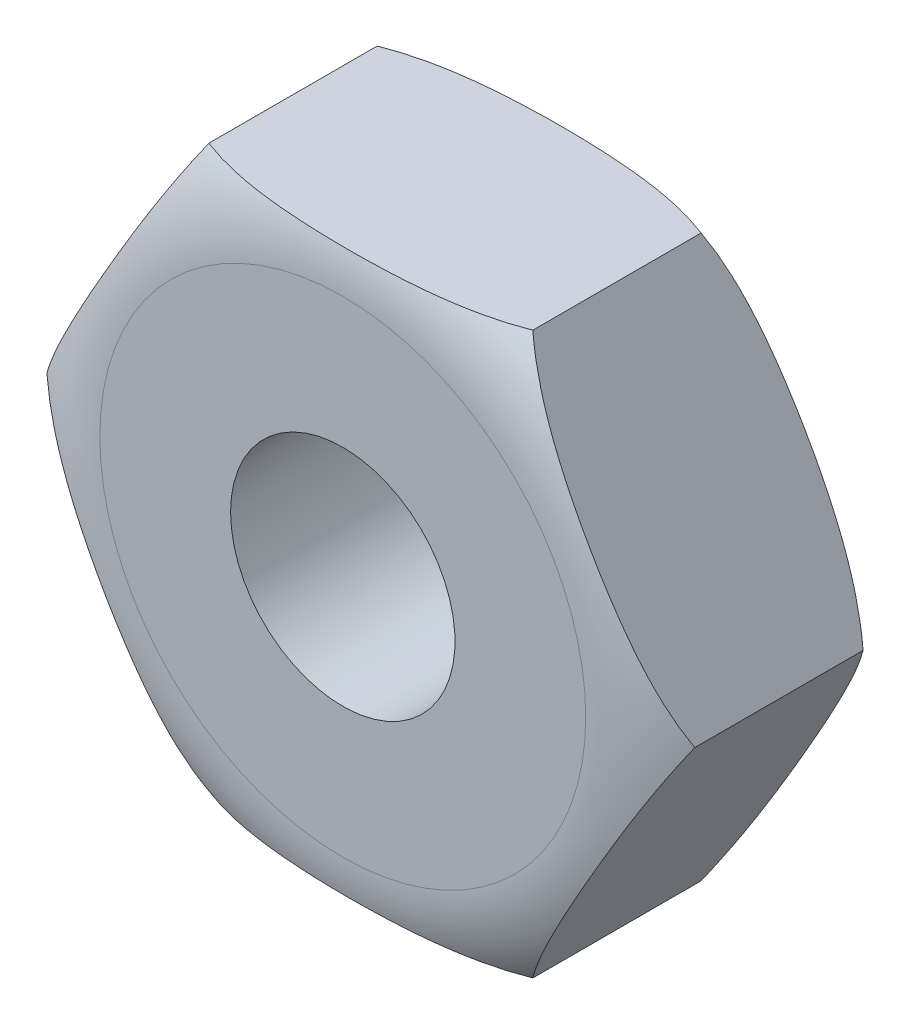
SolidWorks part; units mm, degrees
material "AISI 304"
ref_plane "前视基准面" through (0, 0, 0) normal (0, 0, 1) x (1, 0, 0)
ref_plane "上视基准面" through (0, 0, 0) normal (0, 1, 0) x (1, 0, 0)
ref_plane "右视基准面" through (0, 0, 0) normal (1, 0, 0) x (0, 0, -1)
sketch "草图1" plane through (0, 0, 0) normal (0, 0, 1) x (1, 0, 0)
  line L1 (1.1547, 2) -> (-1.1547, 2)
  line L2 (-1.1547, 2) -> (-2.3094, 0)
  line L3 (-2.3094, 0) -> (-1.1547, -2)
  line L4 (-1.1547, -2) -> (1.1547, -2)
  line L5 (1.1547, -2) -> (2.3094, 0)
  line L6 (2.3094, 0) -> (1.1547, 2)
  circle A0 centre (0, 0) radius 2 construction
  dimension "六角对边" = 4
extrude "螺母的厚度" add sketch "草图1" along normal mid plane 1.6
sketch "草图2" plane through (0, 0, 0) normal (0, 1, 0) x (1, 0, 0)
  line L0 (2.3094, -0.8) -> (2.3094, 0.8) construction
  line L2 (1.7321, 0.8) -> (2.3094, 0.8)
  line L3 (2.3094, 0.8) -> (2.3094, 0.6)
  line L4 (0, 0) -> (0, 0.9918) construction
  line L5 (0, 0) -> (1.8404, 0) construction
  line L6 (2.3094, -0.8) -> (2.3094, -0.6)
  line L7 (1.7321, -0.8) -> (2.3094, -0.8)
  line L8 (2.3094, -0.8) -> (1.1547, -0.8) construction
  arc A0 (2.3094, 0.6) -> (1.7321, 0.8) centre (1.7321, -0.1333) ccw
  arc A1 (2.3094, -0.6) -> (1.7321, -0.8) centre (1.7321, 0.1333) cw
  dimension "D2" = 0.2
revolve "切除-旋转1" cut sketch "草图2" angle 360 about L4
hole_wizard " 螺纹孔1" positions "草图3" profile "草图4" tap size "M1.6" standard "GB" end condition through all
sketch "草图3" plane through (0, 0, -0.8) normal (0, 0, -1) x (-1, 0, 0)
  point P0 (0, 0)
cosmetic thread "孔螺蚊线1" parameters "D2"=3.3
sketch "草图4" plane through (0, 0, -0.8) normal (1, 0, 0) x (0, 1, 0)
  line L0 (0, 0) -> (0, 1.6)
  line L1 (0, 1.6) -> (0.8, 1.6)
  line L2 (0.8, 1.6) -> (0.8, 0)
  line L5 (0.8, 0) -> (0, 0)
  line L11 (0, -6.35) -> (0, 107.95) construction
  dimension "通孔螺纹孔钻头直径" = 1.6
  dimension "通孔螺纹孔钻头深度" = 1.6
